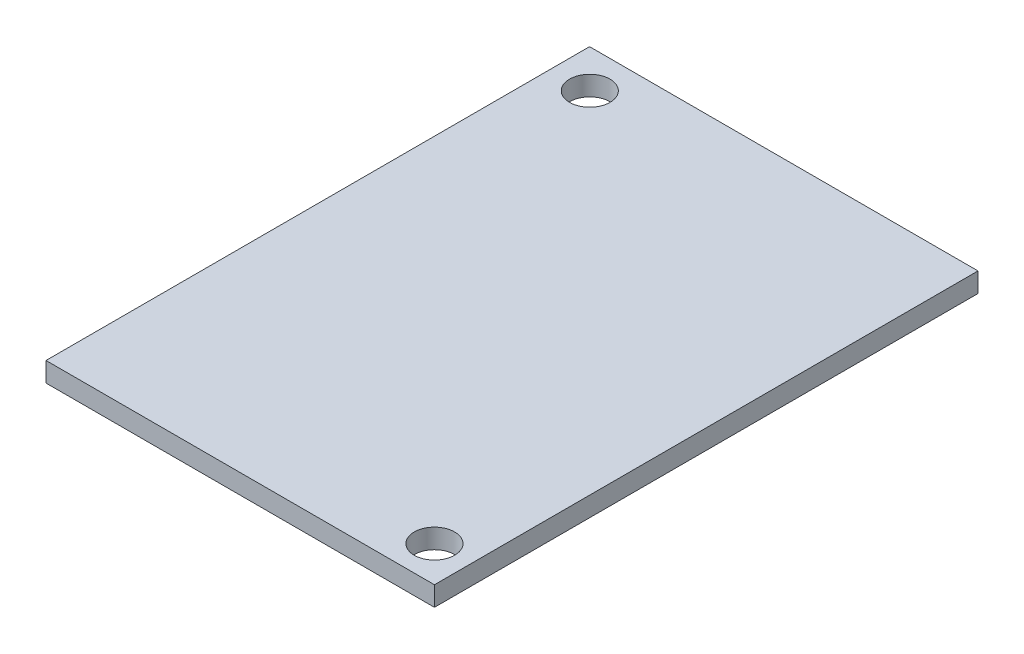
SolidWorks part; units mm, degrees
ref_plane "Front Plane" through (0, 0, 0) normal (0, 0, 1) x (1, 0, 0)
ref_plane "Top Plane" through (0, 0, 0) normal (0, 1, 0) x (1, 0, 0)
ref_plane "Right Plane" through (0, 0, 0) normal (1, 0, 0) x (0, 0, -1)
sketch "Sketch1" plane through (0, 0, 0) normal (0, 1, 0) x (1, 0, 0)
  line L1 (0, 0) -> (31.73, 0)
  line L2 (0, 0) -> (0, 44.4)
  line L3 (0, 44.4) -> (31.73, 44.4)
  line L4 (31.73, 0) -> (31.73, 44.4)
  dimension "D1" = 31.73
  dimension "D2" = 44.4
extrude "Boss-Extrude1" add sketch "Sketch1" along normal blind 1.6
sketch "Sketch2" plane through (0, 1.6, 0) normal (0, 1, 0) x (1, 0, 0)
  line L0 (0, 44.4) -> (0, 0) construction
  line L1 (31.73, 44.4) -> (0, 44.4) construction
  line L2 (31.73, 0) -> (31.73, 44.4) construction
  line L3 (0, 0) -> (31.73, 0) construction
  circle A0 centre (3.13, 41.29) radius 1.65
  circle A1 centre (28.82, 2.91) radius 1.65
  dimension "D1" = 3.3
  dimension "D2" = 3.13
  dimension "D3" = 3.11
  dimension "D4" = 2.91
  dimension "D5" = 2.91
extrude "Cut-Extrude1" cut sketch "Sketch2" against normal through all
